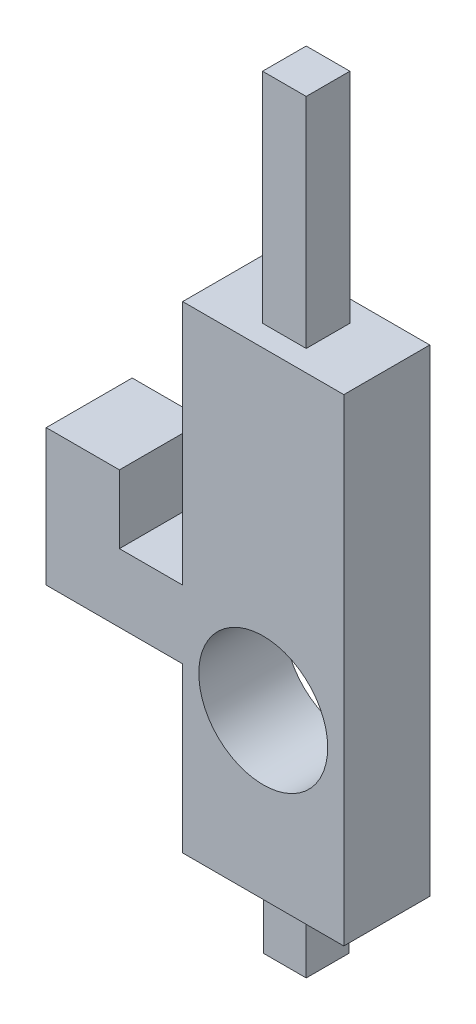
SolidWorks part; units mm, degrees
ref_plane "Front Plane" through (0, 0, 0) normal (0, 0, 1) x (1, 0, 0)
ref_plane "Top Plane" through (0, 0, 0) normal (0, 1, 0) x (1, 0, 0)
ref_plane "Right Plane" through (0, 0, 0) normal (1, 0, 0) x (0, 0, -1)
sketch "Sketch1" plane through (0, 0, 0) normal (0, 1, 0) x (1, 0, 0)
  line L1 (-1.9799, 1.9799) -> (1.9799, 1.9799)
  line L2 (-1.9799, 1.9799) -> (-1.9799, -1.9799)
  line L3 (-1.9799, -1.9799) -> (1.9799, -1.9799)
  line L4 (1.9799, 1.9799) -> (1.9799, -1.9799)
  line L5 (-1.9799, 1.9799) -> (1.9799, -1.9799) construction
  line L6 (-1.9799, -1.9799) -> (1.9799, 1.9799) construction
  circle A0 centre (0, 0) radius 2.8 construction
  dimension "D1" = 5.6
extrude "Boss-Extrude1" add sketch "Sketch1" along normal blind 6.35
sketch "Sketch2" plane through (0, 6.35, 0) normal (0, 1, 0) x (1, 0, 0)
  line L1 (-7.5, 4) -> (7.5, 4)
  line L2 (-7.5, 4) -> (-7.5, -4)
  line L3 (-7.5, -4) -> (7.5, -4)
  line L4 (7.5, 4) -> (7.5, -4)
  line L5 (-7.5, 4) -> (7.5, -4) construction
  line L6 (-7.5, -4) -> (7.5, 4) construction
  point P0 (0, 0)
  dimension "D1" = 8
  dimension "D2" = 15
extrude "Boss-Extrude2" add sketch "Sketch2" along normal blind 44.45
sketch "Sketch3" plane through (0, 0, 4) normal (0, 0, 1) x (1, 0, 0)
  line L0 (0, 50.8) -> (0, -2.7923) construction
  line L1 (-7.5, 50.8) -> (7.5, 50.8) construction
  line L2 (-1.9799, 0) -> (1.9799, 0) construction
  circle A0 centre (0, 21.59) radius 6
  dimension "D2" = 12
  dimension "D1" = 21.59
extrude "Cut-Extrude1" cut sketch "Sketch3" against normal blind 25.4
sketch "Sketch4" plane through (0, 50.8, 0) normal (0, 1, 0) x (1, 0, 0)
  line L1 (-2.032, 2.032) -> (2.032, 2.032)
  line L2 (-2.032, 2.032) -> (-2.032, -2.032)
  line L3 (-2.032, -2.032) -> (2.032, -2.032)
  line L4 (2.032, 2.032) -> (2.032, -2.032)
  line L5 (-2.032, 2.032) -> (2.032, -2.032) construction
  line L6 (-2.032, -2.032) -> (2.032, 2.032) construction
  point P0 (0, 0)
  dimension "D1" = 4.064
  dimension "D2" = 4.064
extrude "Boss-Extrude3" add sketch "Sketch4" along normal blind 20.32
sketch "Sketch5" plane through (-7.5, 0, 0) normal (-1, 0, 0) x (0, 0, 1)
  line L0 (4, 50.8) -> (4, 6.35) construction
  line L1 (-4, 21.59) -> (4, 21.59)
  line L2 (-4, 21.59) -> (-4, 27.94)
  line L3 (-4, 27.94) -> (4, 27.94)
  line L4 (4, 21.59) -> (4, 27.94)
  line L5 (-4, 21.59) -> (4, 27.94) construction
  line L6 (-4, 27.94) -> (4, 21.59) construction
  line L7 (-1.9799, 0) -> (1.9799, 0) construction
  point P0 (0, 24.765)
  dimension "D1" = 6.35
  dimension "D2" = 21.59
extrude "Boss-Extrude4" add sketch "Sketch5" along normal blind 12.7
sketch "Sketch6" plane through (0, 27.94, 0) normal (0, 1, 0) x (1, 0, 0)
  line L1 (-13.3877, -4) -> (-20.2, -4)
  line L2 (-13.3877, -4) -> (-13.3877, 4)
  line L3 (-13.3877, 4) -> (-20.2, 4)
  line L4 (-20.2, -4) -> (-20.2, 4)
  line L5 (-13.3877, -4) -> (-20.2, 4) construction
  line L6 (-13.3877, 4) -> (-20.2, -4) construction
  point P0 (-16.7938, 0)
extrude "Boss-Extrude5" add sketch "Sketch6" along normal blind 6.35
